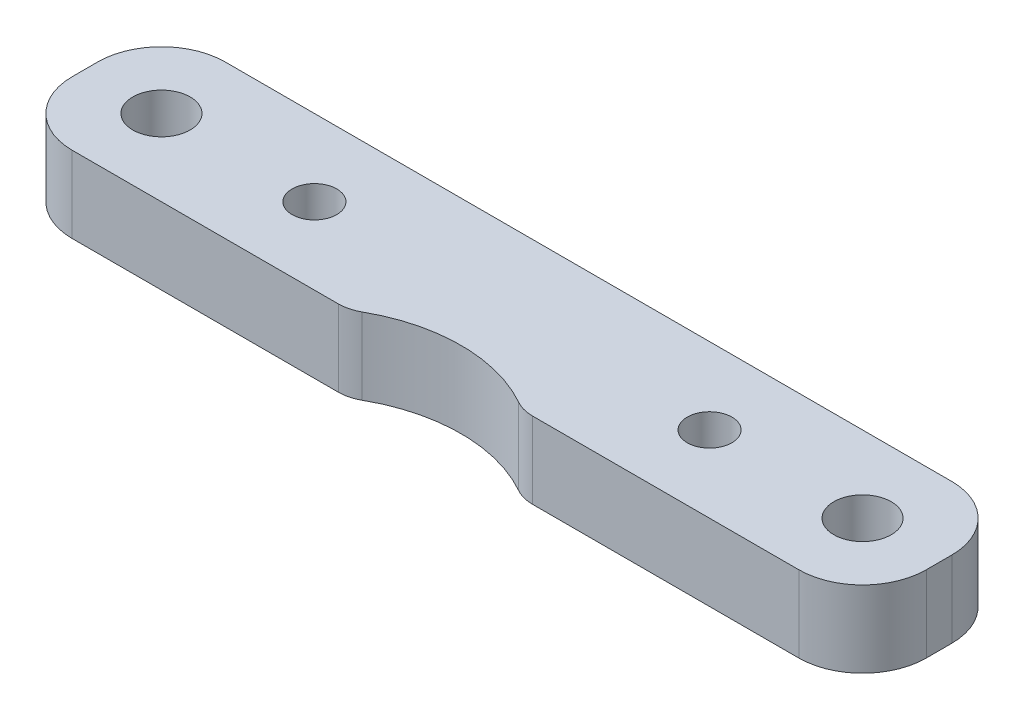
SolidWorks part; units mm, degrees
material "3D printed plastic"
ref_plane "Front Plane" through (0, 0, 0) normal (0, 0, 1) x (1, 0, 0)
ref_plane "Top Plane" through (0, 0, 0) normal (0, 1, 0) x (1, 0, 0)
ref_plane "Right Plane" through (0, 0, 0) normal (1, 0, 0) x (0, 0, -1)
sketch "Sketch1" plane through (0, 0, 0) normal (0, 1, 0) x (1, 0, 0)
  line L0 (-27.5, 0) -> (-15.5, 0) construction
  line L1 (-15.5, 0) -> (15.5, 0) construction
  line L2 (15.5, 0) -> (27.5, 0) construction
  line L3 (27.5, 6) -> (27.5, 0) construction
  line L4 (-28.5, 6) -> (28.5, 6)
  line L5 (-33.5, 1) -> (-33.5, -1)
  line L6 (-28.5, -6) -> (-7.6158, -6)
  line L7 (33.5, 1) -> (33.5, -1)
  line L8 (27.5, 0) -> (33.5, 0) construction
  line L9 (-27.5, 0) -> (-33.5, 0) construction
  line L10 (7.6158, -6) -> (28.5, -6)
  line L11 (0, 0) -> (0, -16.5) construction
  circle A0 centre (-15.5, 0) radius 1.75
  circle A1 centre (15.5, 0) radius 1.75
  circle A2 centre (27.5, 0) radius 2.25
  circle A3 centre (-27.5, 0) radius 2.25
  arc A4 (28.5, 6) -> (33.5, 1) centre (28.5, 1) cw
  arc A5 (-33.5, -1) -> (-28.5, -6) centre (-28.5, -1) ccw
  arc A6 (28.5, -6) -> (33.5, -1) centre (28.5, -1) ccw
  arc A7 (-28.5, 6) -> (-33.5, 1) centre (-28.5, 1) ccw
  arc A8 (6.1418, -5.6129) -> (-6.1418, -5.6129) centre (0, -16.5) ccw
  arc A9 (6.1418, -5.6129) -> (7.6158, -6) centre (7.6158, -3) ccw
  arc A10 (-6.1418, -5.6129) -> (-7.6158, -6) centre (-7.6158, -3) cw
  point P18 (33.5, 6)
  point P23 (33.5, -6)
  point P32 (6.7823, -6)
  dimension "D2" = 55
  dimension "D3" = 4.5
  dimension "D4" = 3.5
  dimension "D6" = 5
  dimension "D7" = 12.5
  dimension "D9" = 3
  dimension "D1" = 31
  dimension "D5" = 12
  dimension "D8" = 16.5
extrude "Boss-Extrude1" add sketch "Sketch1" along normal blind 6
